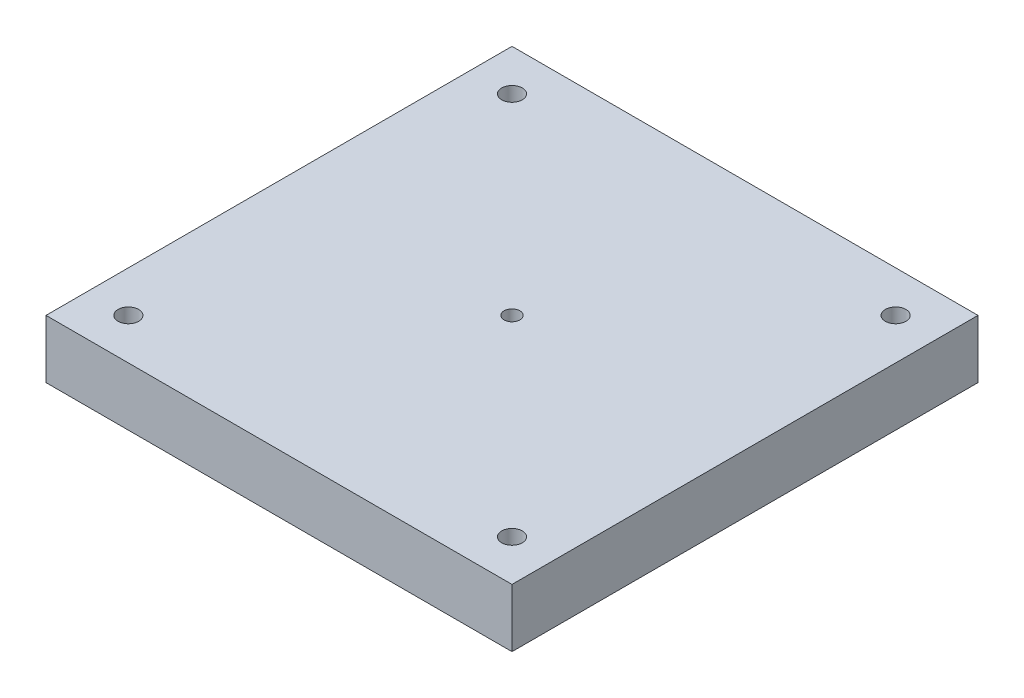
SolidWorks part; units mm, degrees
material "6061 Alloy"
ref_plane "Front Plane" through (0, 0, 0) normal (0, 0, 1) x (1, 0, 0)
ref_plane "Top Plane" through (0, 0, 0) normal (0, 1, 0) x (1, 0, 0)
ref_plane "Right Plane" through (0, 0, 0) normal (1, 0, 0) x (0, 0, -1)
sketch "Sketch1" plane through (0, 0, 0) normal (0, 1, 0) x (1, 0, 0)
  line L1 (-50.8, 50.8) -> (50.8, 50.8)
  line L2 (-50.8, 50.8) -> (-50.8, -50.8)
  line L3 (-50.8, -50.8) -> (50.8, -50.8)
  line L4 (50.8, 50.8) -> (50.8, -50.8)
  line L5 (-50.8, 50.8) -> (50.8, -50.8) construction
  line L6 (-50.8, -50.8) -> (50.8, 50.8) construction
  point P0 (0, 0)
  point P6 (0, 0)
  dimension "D1" = 101.6
  dimension "D2" = 101.6
extrude "Boss-Extrude1" add sketch "Sketch1" against normal blind 12.7
sketch "Sketch3" plane through (0, 0, 0) normal (0, 1, 0) x (1, 0, 0)
  line L0 (-50.8, 50.8) -> (50.8, -50.8) construction
  circle A2 centre (-41.8197, 41.8197) radius 2.2479
  circle A3 centre (0, 0) radius 10.1224 construction
  circle A4 centre (41.8197, 41.8197) radius 2.2479
  circle A5 centre (41.8197, -41.8197) radius 2.2479
  circle A6 centre (-41.8197, -41.8197) radius 2.2479
  circle A7 centre (0, 0) radius 1.7272
  point P22 (0, 0)
  dimension "D1" = 3.4544
  dimension "D3" = 4.4958
  dimension "D4" = 12.7
  dimension "D5" = 4
extrude "Cut-Extrude1" cut sketch "Sketch3" against normal through all
